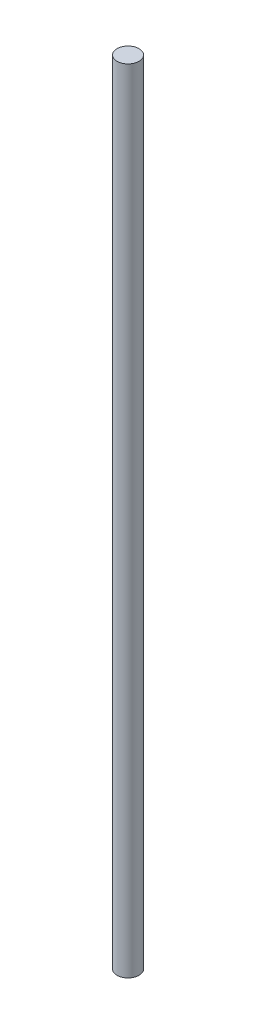
SolidWorks part; units mm, degrees
ref_plane "Спереди" through (0, 0, 0) normal (0, 0, 1) x (1, 0, 0)
ref_plane "Сверху" through (0, 0, 0) normal (0, 1, 0) x (1, 0, 0)
ref_plane "Справа" through (0, 0, 0) normal (1, 0, 0) x (0, 0, -1)
sketch "Эскиз1" plane through (0, 0, 0) normal (0, 1, 0) x (1, 0, 0)
  circle A0 centre (0, 0) radius 2.5
  dimension "D1" = 5
extrude "Бобышка-Вытянуть1" add sketch "Эскиз1" along normal blind 180
equation "\"motor_diameter\"= 30"
equation "\"mm_diameter\"= IIF ( \"motor_diameter\" < 34 , 41 , \"motor_diameter\" + 8 )"
equation "\"upper_shafts_diameter\"= 5"
equation "\"upper_shats_length\"= 180"
equation "\"upper_bearing_d1\"= 10"
equation "\"upper_bearing_d2\"= 5"
equation "\"upper_bearing_h\"= 15"
equation "\"lower_shafts_diameter\"= 5"
equation "\"lower_shafts_length\"= 180"
equation "\"lower_bearing_d1\"= 10"
equation "\"lower_bearing_d2\"= 5"
equation "\"lower_bearing_h\"= 15"
equation "\"print_offset\"= 0.2"
equation "\"bh_screws_d\"= 2"
equation "\"bh_screws_h\"= 20"
equation "\"bh_screws_hh_d\"= 3.4"
equation "\"bh_screws_hh_h\"= 2"
equation "\"bh_nut_d\"= 3.8"
equation "\"bh_nut_h\"= 2"
equation "\"motor_screws_d\"= 3"
equation "\"motor_screws_h\"= 16"
equation "\"motor_screws_hh_d\"= 5.5"
equation "\"motor_screws_hh_h\"= 3"
equation "\"plate_hole_distance\"= 25.4"
equation "\"plate_screws_d\"= 6.5"
equation "\"D1@Эскиз1\" = \"upper_shafts_diameter\""
equation "\"D1@Бобышка-Вытянуть1\"= \"upper_shats_length\""
